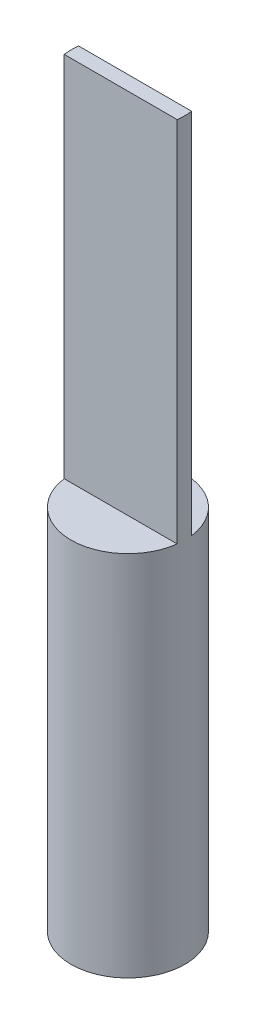
SolidWorks part; units mm, degrees
ref_plane "Front Plane" through (0, 0, 0) normal (0, 0, 1) x (1, 0, 0)
ref_plane "Top Plane" through (0, 0, 0) normal (0, 1, 0) x (1, 0, 0)
ref_plane "Right Plane" through (0, 0, 0) normal (1, 0, 0) x (0, 0, -1)
sketch "Sketch1" plane through (0, 0, 0) normal (0, 1, 0) x (1, 0, 0)
  circle A0 centre (0, 0) radius 3.937
  dimension "D1" = 7.874
extrude "Boss-Extrude1" add sketch "Sketch1" along normal blind 50.8
sketch "Sketch2" plane through (0, 50.8, 0) normal (0, 1, 0) x (1, 0, 0)
  line L0 (-4.5218, 0) -> (4.9849, 0) construction
  line L1 (5.4752, -4.2449) -> (5.4752, -0.5)
  line L2 (-4.8578, 4.2449) -> (5.4752, 4.2449)
  line L3 (-4.8578, 4.2449) -> (-4.8578, 0.5)
  line L4 (-4.8578, 0.5) -> (5.4752, 0.5)
  line L5 (5.4752, 4.2449) -> (5.4752, 0.5)
  line L6 (-4.8578, -0.5) -> (5.4752, -0.5)
  line L7 (-4.8578, -4.2449) -> (-4.8578, -0.5)
  line L8 (-4.8578, -4.2449) -> (5.4752, -4.2449)
  dimension "D1" = 1
extrude "Cut-Extrude1" cut sketch "Sketch2" against normal blind 25.4
